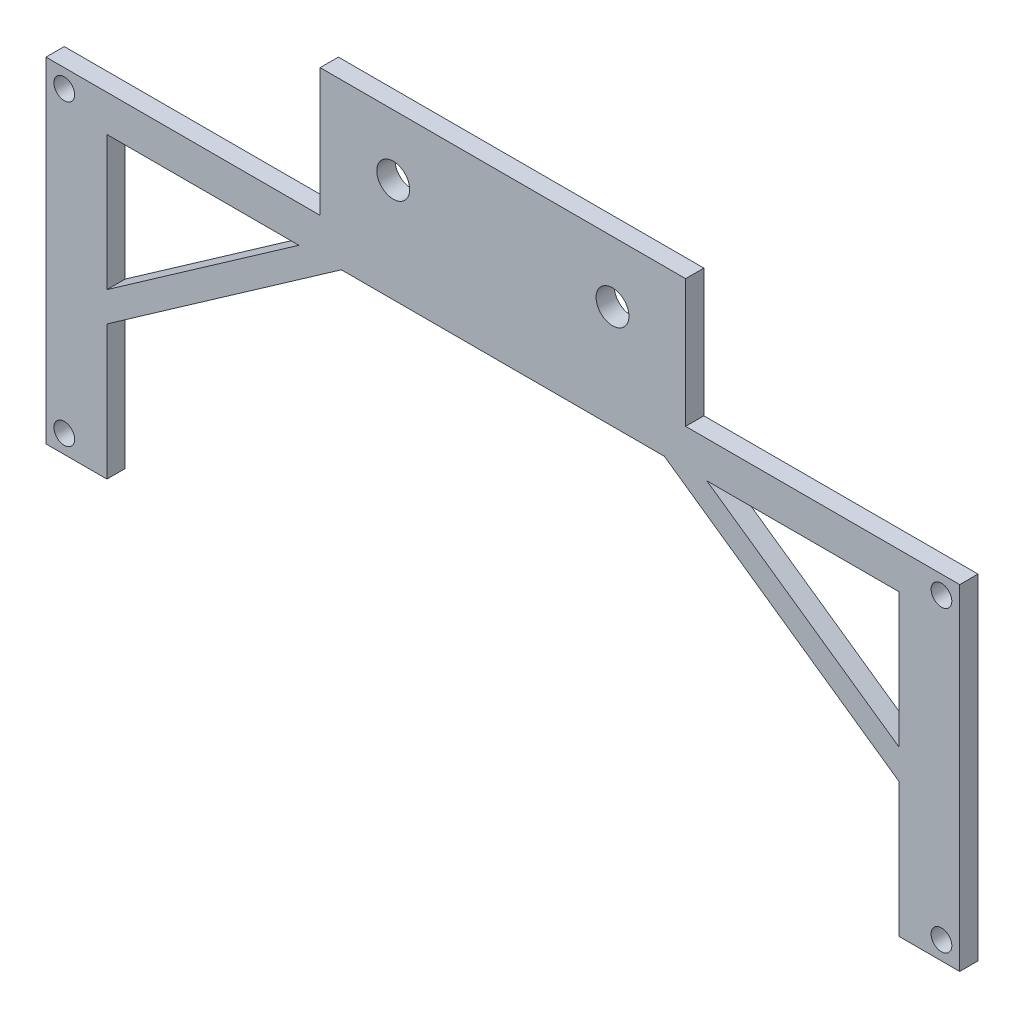
SolidWorks part; units mm, degrees
ref_plane "前基準面" through (0, 0, 0) normal (0, 0, 1) x (1, 0, 0)
ref_plane "上基準面" through (0, 0, 0) normal (0, 1, 0) x (1, 0, 0)
ref_plane "右基準面" through (0, 0, 0) normal (1, 0, 0) x (0, 0, -1)
sketch "草圖1" plane through (0, 0, 0) normal (0, 0, 1) x (1, 0, 0)
  line L1 (-30, 13.5) -> (30, 13.5)
  line L2 (-30, 13.5) -> (-30, -13.5)
  line L3 (-30, -13.5) -> (30, -13.5)
  line L4 (30, 13.5) -> (30, -13.5)
  point P4 (0, 13.5)
  point P6 (-30, 0)
  dimension "D1" = 27
  dimension "D2" = 60
extrude "填料-伸長1" add sketch "草圖1" along normal blind 3
sketch "草圖2" plane through (0, 0, 3) normal (0, 0, 1) x (1, 0, 0)
  line L0 (-30, -13.5) -> (30, -13.5) construction
  line L1 (-75, -7.5) -> (75, -7.5)
  line L2 (-75, -7.5) -> (-75, -13.5)
  line L3 (-75, -13.5) -> (75, -13.5)
  line L4 (75, -7.5) -> (75, -13.5)
  point P4 (0, -7.5)
  dimension "D1" = 150
  dimension "D2" = 6
extrude "填料-伸長2" add sketch "草圖2" against normal up to surface (3 mm away) up to face at (0, 0, 0)
sketch "草圖3" plane through (0, 0, 3) normal (0, 0, 1) x (1, 0, 0)
  line L0 (0, 13.5) -> (0, -13.5) construction
  line L1 (30, 13.5) -> (-30, 13.5) construction
  line L2 (-75, -13.5) -> (75, -13.5) construction
  line L3 (65, -62.5) -> (75, -62.5)
  line L4 (-75, -7.5) -> (75, -7.5)
  line L5 (-75, -7.5) -> (-75, -62.5)
  line L6 (-75, -62.5) -> (-65, -62.5)
  line L7 (75, -7.5) -> (75, -62.5)
  line L8 (-65, -13.5) -> (65, -13.5)
  line L9 (-65, -13.5) -> (-65, -62.5)
  line L11 (65, -13.5) -> (65, -62.5)
  point P15 (0, -13.5)
  dimension "D1" = 55
  dimension "D2" = 130
extrude "填料-伸長3" add sketch "草圖3" against normal up to surface (3 mm away) up to face at (0, -3.75, 0)
sketch "草圖4" plane through (0, 0, 3) normal (0, 0, 1) x (1, 0, 0)
  line L0 (-30, -7.5) -> (-75, -7.5) construction
  line L1 (-75, -7.5) -> (-75, -62.5) construction
  line L2 (0, 13.5) -> (0, -62.5) construction
  line L3 (30, 13.5) -> (-30, 13.5) construction
  line L4 (-75, -35) -> (75, -35) construction
  line L5 (75, -62.5) -> (75, -7.5) construction
  circle A0 centre (-72, -10.5) radius 1.7
  circle A1 centre (-72, -59.5) radius 1.7
  circle A2 centre (72, -59.5) radius 1.7
  circle A3 centre (72, -10.5) radius 1.7
  dimension "D3" = 3.4
  dimension "D1" = 3
  dimension "D2" = 3
extrude "除料-伸長1" cut sketch "草圖4" against normal through all
sketch "草圖5" plane through (0, 0, 3) normal (0, 0, 1) x (1, 0, 0)
  line L0 (-65, -38) -> (-30, -13.5) construction
  line L1 (-65, -62.5) -> (-65, -13.5) construction
  line L2 (-65, -13.5) -> (65, -13.5) construction
  line L3 (0, -13.5) -> (0, 13.5) construction
  line L4 (30, 13.5) -> (-30, 13.5) construction
  line L5 (-63.8531, -39.6385) -> (-28.8531, -15.1385)
  line L6 (-65, -35.5587) -> (-33.4876, -13.5)
  line L7 (65, -38) -> (30, -13.5) construction
  line L8 (26.5124, -13.5) -> (33.4876, -13.5)
  line L9 (-63.8531, -39.6385) -> (-65, -40.4413)
  line L10 (-65, -40.4413) -> (-65, -38)
  line L11 (-65, -38) -> (-65, -35.5587)
  line L12 (-28.8531, -15.1385) -> (-26.5124, -13.5)
  line L13 (-26.5124, -13.5) -> (-33.4876, -13.5)
  line L14 (-66.1469, -36.3615) -> (-31.1469, -11.8615) construction
  line L15 (28.8531, -15.1385) -> (26.5124, -13.5)
  line L16 (65, -38) -> (65, -35.5587)
  line L17 (65, -40.4413) -> (65, -38)
  line L18 (63.8531, -39.6385) -> (65, -40.4413)
  line L19 (65, -35.5587) -> (33.4876, -13.5)
  line L20 (63.8531, -39.6385) -> (28.8531, -15.1385)
  dimension "D1" = 2
  dimension "D2" = 2
extrude "填料-伸長4" add sketch "草圖5" against normal up to surface (3 mm away) up to face at (-73.7, -59.5, 0)
sketch "草圖6" plane through (0, 0, 3) normal (0, 0, 1) x (1, 0, 0)
  line L0 (0, -13.5) -> (0, 13.5) construction
  line L1 (-26.5124, -13.5) -> (26.5124, -13.5) construction
  line L2 (30, 13.5) -> (-30, 13.5) construction
  circle A0 centre (-18, 3.5) radius 2.7
  circle A1 centre (18, 3.5) radius 2.7
  dimension "D2" = 5.4
  dimension "D1" = 18
  dimension "D3" = 10
extrude "除料-伸長2" cut sketch "草圖6" against normal through all
